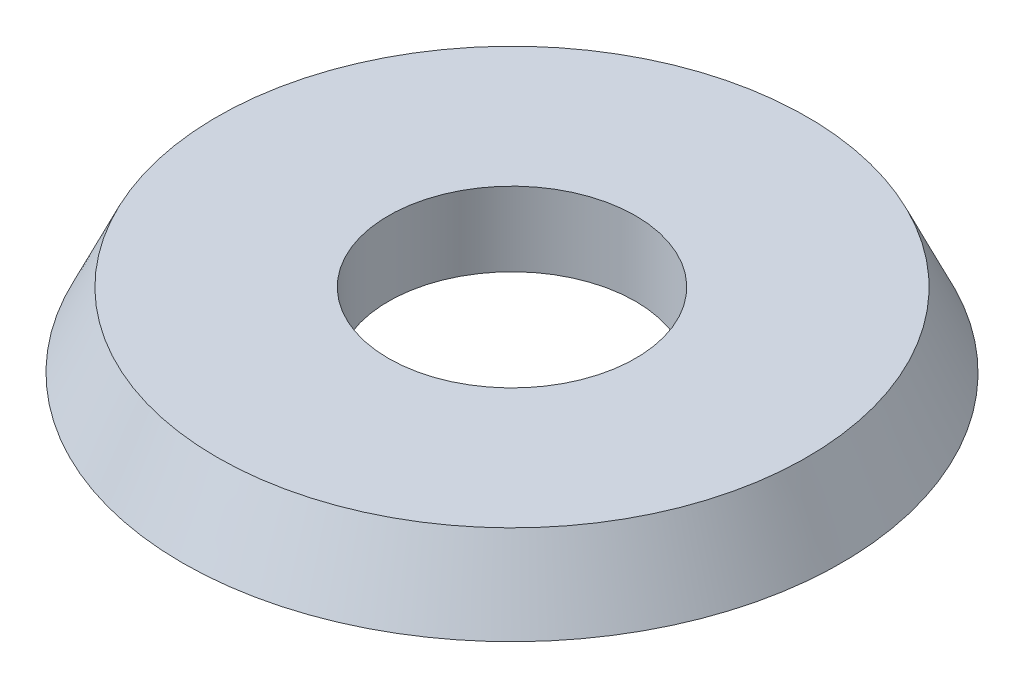
SolidWorks part; units mm, degrees
ref_plane "Front Plane" through (0, 0, 0) normal (0, 0, 1) x (1, 0, 0)
ref_plane "Top Plane" through (0, 0, 0) normal (0, 1, 0) x (1, 0, 0)
ref_plane "Right Plane" through (0, 0, 0) normal (1, 0, 0) x (0, 0, -1)
sketch "Sketch1" plane through (0, 0, 0) normal (0, 0, 1) x (1, 0, 0)
  line L0 (0, 0) -> (0, -13088.1161) construction
  line L1 (0, 0) -> (-13088.1161, 0) construction
  line L2 (-7.5, 0) -> (-7.5, 4.5)
  line L3 (-7.5, 4.5) -> (-17.9, 4.5)
  line L4 (-17.9, 4.5) -> (-20, 0)
  line L5 (-20, 0) -> (-7.5, 0)
  dimension "D1" = 40
  dimension "D2" = 35.8
  dimension "D3" = 4.5
  dimension "D4" = 15
revolve "Revolve1" add sketch "Sketch1" angle 360 about L0
